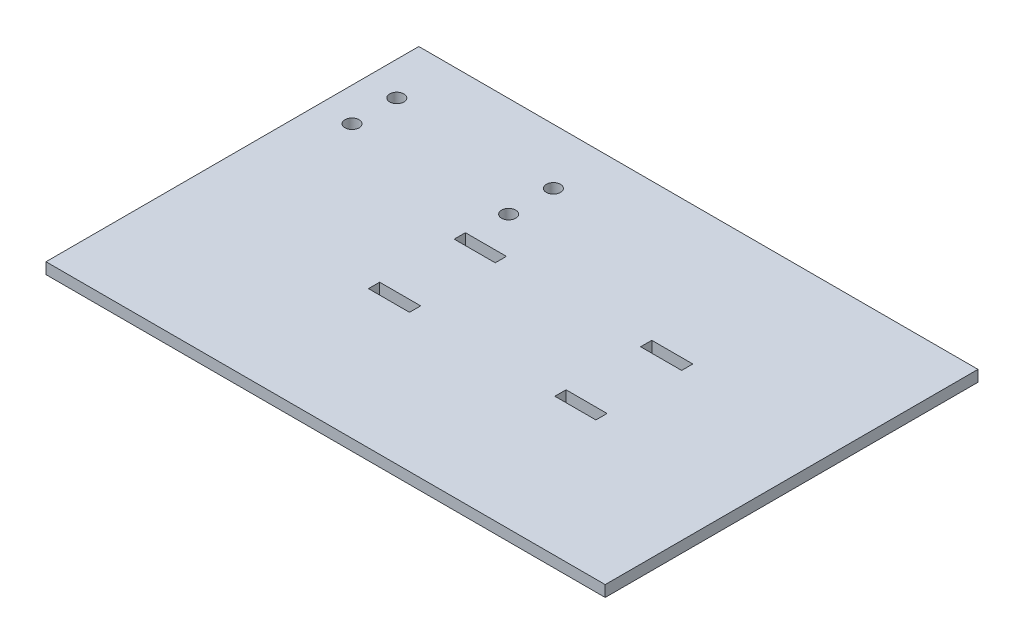
SolidWorks part; units mm, degrees
material "Acrylic (Medium-high impact)"
ref_plane "Front Plane" through (0, 0, 0) normal (0, 0, 1) x (1, 0, 0)
ref_plane "Top Plane" through (0, 0, 0) normal (0, 1, 0) x (1, 0, 0)
ref_plane "Right Plane" through (0, 0, 0) normal (1, 0, 0) x (0, 0, -1)
sketch "Sketch1" plane through (0, 0, 0) normal (0, 1, 0) x (1, 0, 0)
  line L1 (-30, 50) -> (120, 50)
  line L2 (-30, 50) -> (-30, -50)
  line L3 (-30, -50) -> (120, -50)
  line L4 (120, 50) -> (120, -50)
  line L5 (-30, 50) -> (120, -50) construction
  line L6 (-30, -50) -> (120, 50) construction
  point P0 (45, 0)
  point P6 (-30, 0)
  dimension "D1" = 100
  dimension "D2" = 150
  dimension "D3" = 30
extrude "BasePlate" add sketch "Sketch1" against normal blind 3
hole_wizard "#6 Clearance Hole1" positions "Sketch3" profile "Sketch2" hole size "#6" standard "ANSI Inch" end condition through all
sketch "Sketch3" plane through (0, 0, 0) normal (0, 1, 0) x (1, 0, 0)
  line L0 (-21, 35.1) -> (21, 35.1) construction
  line L1 (21, 35.1) -> (21, 23.1) construction
  line L2 (21, 23.1) -> (-21, 23.1) construction
  line L3 (-21, 23.1) -> (-21, 35.1) construction
  point P0 (-21, 23.1)
  point P2 (21, 23.1)
  point P4 (21, 35.1)
  point P6 (-21, 35.1)
  dimension "D1" = 23.1
  dimension "D2" = 42
  dimension "D3" = 12
  dimension "D4" = 21
sketch "Sketch2" plane through (-21, 0, -23.1) normal (1, 0, 0) x (0, 0, 1)
  line L0 (0, 0) -> (0, 3)
  line L1 (0, 3) -> (1.8986, 3)
  line L2 (1.8986, 3) -> (1.8986, 0)
  line L5 (1.8986, 0) -> (0, 0)
  line L11 (0, -6.35) -> (0, 107.95) construction
  dimension "Thru Hole Dia." = 3.7973
  dimension "Thru Hole Depth" = 3
sketch "Sketch4" plane through (0, 0, 0) normal (0, 1, 0) x (1, 0, 0)
  line L0 (-1.65, 0) -> (1.65, 0) construction
  line L1 (19.5, 10) -> (30.5, 10)
  line L2 (19.5, 10) -> (19.5, 13)
  line L3 (19.5, 13) -> (30.5, 13)
  line L4 (30.5, 10) -> (30.5, 13)
  line L5 (0, -1.65) -> (0, 1.65) construction
  dimension "D1" = 10
  dimension "D2" = 3
  dimension "D3" = 11
  dimension "D4" = 19.5
extrude "BaseTabHole" cut sketch "Sketch4" against normal through all
pattern_linear "BaseTabHolePattern" count 2 spacing 50 along (1, 0, 0) count 2 spacing 23 along (0, 0, 1) of "BaseTabHole"
sketch "Sketch5" plane through (0, 0, 0) normal (0, 1, 0) x (1, 0, 0)
  line L18 (-30.1442, -50.1442) -> (120.1442, -50.1442)
  line L19 (120.1442, -50.1442) -> (120.1442, 50.1442)
  line L20 (120.1442, 50.1442) -> (-30.1442, 50.1442)
  line L21 (-30.1442, 50.1442) -> (-30.1442, -50.1442)
  line L23 (80.3558, 12.8558) -> (69.6442, 12.8558)
  line L24 (69.6442, 12.8558) -> (69.6442, 10.1442)
  line L25 (69.6442, 10.1442) -> (80.3558, 10.1442)
  line L26 (80.3558, 10.1442) -> (80.3558, 12.8558)
  line L36 (30.3558, 10.1442) -> (30.3558, 12.8558)
  line L37 (19.6442, 10.1442) -> (30.3558, 10.1442)
  line L38 (19.6442, 12.8558) -> (19.6442, 10.1442)
  line L39 (30.3558, 12.8558) -> (19.6442, 12.8558)
  line L54 (19.6442, -12.8558) -> (30.3558, -12.8558)
  line L55 (30.3558, -12.8558) -> (30.3558, -10.1442)
  line L56 (30.3558, -10.1442) -> (19.6442, -10.1442)
  line L57 (19.6442, -10.1442) -> (19.6442, -12.8558)
  line L63 (69.6442, -10.1442) -> (69.6442, -12.8558)
  line L64 (69.6442, -12.8558) -> (80.3558, -12.8558)
  line L65 (80.3558, -12.8558) -> (80.3558, -10.1442)
  line L66 (80.3558, -10.1442) -> (69.6442, -10.1442)
  circle A6 centre (-21, 23.1) radius 1.7545
  circle A9 centre (-21, 35.1) radius 1.7545
  circle A12 centre (21, 35.1) radius 1.7545
  circle A15 centre (21, 23.1) radius 1.7545
extrude "FOR the LASER CUTTER" [suppressed] add sketch "Sketch5" along normal blind 10 separate body
